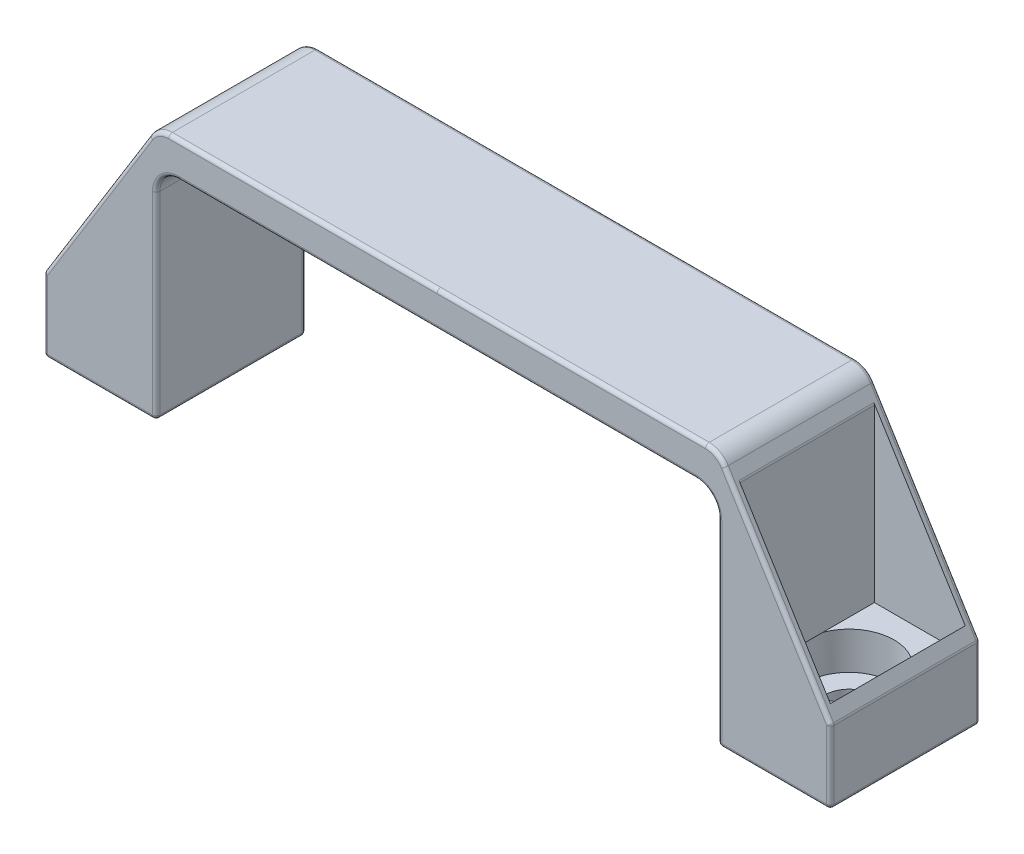
SolidWorks part; units mm, degrees
material "6061 Alloy"
ref_plane "Front Plane" through (0, 0, 0) normal (0, 0, 1) x (1, 0, 0)
ref_plane "Top Plane" through (0, 0, 0) normal (0, 1, 0) x (1, 0, 0)
ref_plane "Right Plane" through (0, 0, 0) normal (1, 0, 0) x (0, 0, -1)
sketch "Sketch1" plane through (0, 0, 0) normal (0, 0, 1) x (1, 0, 0)
  line L0 (0, 0) -> (0, 9.76)
  line L1 (0, 9.76) -> (14.1204, 32.5786)
  line L2 (16.6715, 34) -> (52.5, 34)
  line L3 (52.5, 34) -> (52.5, 29.35)
  line L4 (52.5, 29.35) -> (18, 29.35)
  line L6 (15, 26.35) -> (15, 0)
  line L7 (15, 0) -> (0, 0)
  line L8 (15, 34) -> (15, 29.35) construction
  arc A0 (18, 29.35) -> (15, 26.35) centre (18, 26.35) ccw
  arc A1 (16.6715, 34) -> (14.1204, 32.5786) centre (16.6715, 31) ccw
  dimension "D6" = 3
  dimension "D1" = 9.76
  dimension "D2" = 34
  dimension "D3" = 4.65
  dimension "D4" = 52.5
  dimension "D5" = 15
extrude "Boss-Extrude1" add sketch "Sketch1" along normal blind 20
sketch "Sketch2" plane through (0, 34, 0) normal (0, 1, 0) x (1, 0, 0)
  line L0 (1, -1) -> (13.1204, -1)
  line L1 (13.1204, -1) -> (13.1204, -19)
  line L2 (13.1204, -19) -> (1, -19)
  line L3 (1, -19) -> (1, -1)
  line L4 (14.1204, -20) -> (14.1204, 0) construction
  line L5 (0, -20) -> (0, 0) construction
  line L6 (14.1204, 0) -> (0, 0) construction
  line L7 (14.1204, -20) -> (0, -20) construction
  dimension "D1" = 1
  dimension "D2" = 1
  dimension "D3" = 1
  dimension "D4" = 1
extrude "Cut-Extrude1" cut sketch "Sketch2" against normal blind 26
sketch "Sketch3" plane through (0, 8, 0) normal (0, 1, 0) x (1, 0, 0)
  line L1 (13.1204, -19) -> (1, -19) construction
  line L2 (52.5, -20) -> (52.5, 0) construction
  circle A0 centre (7.5, -10) radius 6
  dimension "D1" = 12
  dimension "D2" = 45
  dimension "D3" = 9
extrude "Cut-Extrude2" cut sketch "Sketch3" against normal blind 5
sketch "Sketch4" plane through (0, 3, 0) normal (0, 1, 0) x (1, 0, 0)
  line L0 (52.5, -20) -> (52.5, 0) construction
  line L1 (14.1204, -20) -> (0, -20) construction
  circle A0 centre (7.5, -10) radius 3.25
  dimension "D1" = 6.5
  dimension "D2" = 45
  dimension "D3" = 10
extrude "Cut-Extrude3" cut sketch "Sketch4" against normal up to next
fillet "Fillet3" radius 0.5 20 edges at (15.2113, 33.6207, 0) (15.2113, 33.6207, 20) (15.8787, 28.4713, 0) (15.8787, 28.4713, 20) (13.1204, 30.9626, 10) (0, 4.88, 0) (0, 4.88, 20) (0, 9.76, 10) (7.0602, 21.1693, 0) (7.0602, 21.1693, 20) (34.5858, 34, 0) (34.5858, 34, 20) (35.25, 29.35, 0) (35.25, 29.35, 20) (15, 13.175, 0) (15, 13.175, 20) (7.5, 0, 0) (0, 0, 10) (7.5, 0, 20) (15, 0, 10)
mirror "Mirror1" about plane through (52.5, 34, 20) normal (-1, 0, 0) of "Fillet3", "Cut-Extrude3", "Cut-Extrude2", "Cut-Extrude1", "Boss-Extrude1"
